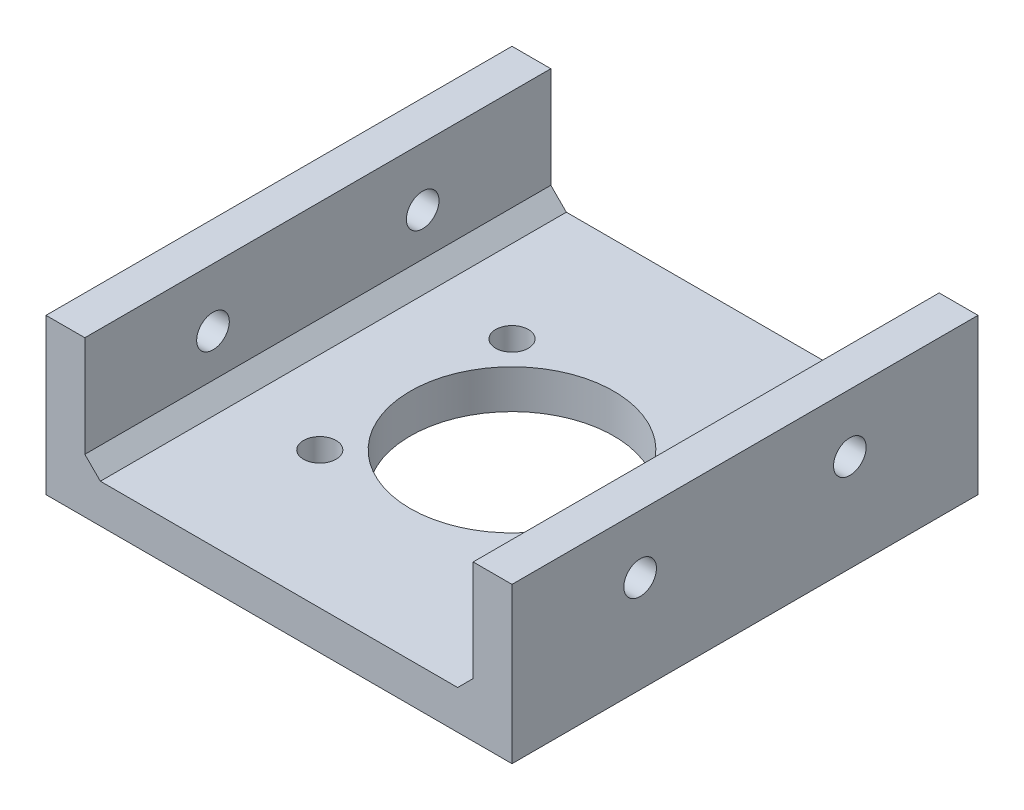
SolidWorks part; units mm, degrees
ref_plane "前视基准面" through (0, 0, 0) normal (0, 0, 1) x (1, 0, 0)
ref_plane "上视基准面" through (0, 0, 0) normal (0, 1, 0) x (1, 0, 0)
ref_plane "右视基准面" through (0, 0, 0) normal (1, 0, 0) x (0, 0, -1)
sketch "草图1" plane through (0, 0, 0) normal (0, 1, 0) x (1, 0, 0)
  line L0 (-12.3744, -12.3744) -> (0, 0) construction
  line L1 (-30, -30) -> (30, -30)
  line L2 (-30, -30) -> (-30, 30)
  line L3 (-30, 30) -> (30, 30)
  line L4 (30, -30) -> (30, 30)
  line L5 (0, 30) -> (0, -30) construction
  line L6 (-30, 0) -> (30, 0) construction
  circle A0 centre (0, 0) radius 13.1
  circle A1 centre (-12.3744, -12.3744) radius 2.1
  circle A2 centre (12.3744, -12.3744) radius 2.1
  circle A3 centre (-12.3744, 12.3744) radius 2.1
  circle A4 centre (12.3744, 12.3744) radius 2.1
  point P0 (0, 0)
  dimension "D3" = 26.2
  dimension "D5" = 4.2
  dimension "D7" = 4.2
  dimension "D8" = 4.2
  dimension "D1" = 60
  dimension "D2" = 60
  dimension "D4" = 17.5
  dimension "D6" = 45
  dimension "D9" = 35
extrude "凸台-拉伸1" add sketch "草图1" along normal blind 5
sketch "草图2" plane through (0, 5, 0) normal (0, 1, 0) x (1, 0, 0)
  line L0 (-30, -30) -> (30, -30) construction
  line L1 (-30, 30) -> (-25, 30)
  line L2 (-30, 30) -> (-30, -30)
  line L3 (-30, -30) -> (-25, -30)
  line L4 (-25, 30) -> (-25, -30)
  line L5 (-12.3744, 12.3744) -> (12.3744, 12.3744) construction
  line L6 (12.3744, 12.3744) -> (12.3744, -12.3744) construction
  line L7 (12.3744, -12.3744) -> (-12.3744, -12.3744) construction
  line L8 (-12.3744, -12.3744) -> (-12.3744, 12.3744) construction
  line L9 (0, 12.3744) -> (0, -12.3744) construction
  line L10 (30, -30) -> (25, -30)
  line L11 (30, 30) -> (30, -30)
  line L12 (30, 30) -> (25, 30)
  line L13 (25, 30) -> (25, -30)
  line L14 (-27.5, 30) -> (-27.5, -30) construction
  line L15 (27.5, -30) -> (27.5, 30) construction
  line L16 (-30, 0) -> (30, 0) construction
  dimension "D1" = 5
extrude "凸台-拉伸2" add sketch "草图2" along normal blind 15
sketch "草图4" plane through (-30, 0, 0) normal (-1, 0, 0) x (0, 0, 1)
  line L3 (0, 20) -> (0, 0) construction
  line L4 (-30, 20) -> (30, 20) construction
  circle A0 centre (-13.5, 12.5) radius 2.1
  circle A1 centre (13.5, 12.5) radius 2.1
  dimension "D1" = 4.2
  dimension "D2" = 13.5
  dimension "D3" = 7.5
extrude "M4通孔" cut sketch "草图4" against normal through all
chamfer "倒角1" distance 2 distance2 2 2 edges at (25, 5, 0) (-25, 5, 0)
